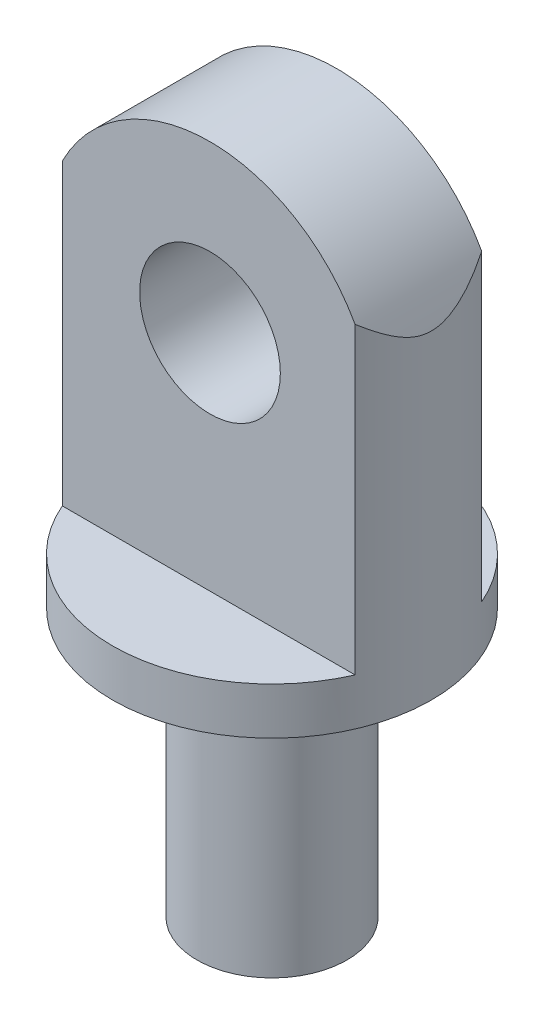
SolidWorks part; units mm, degrees
ref_plane "前视基准面" through (0, 0, 0) normal (0, 0, 1) x (1, 0, 0)
ref_plane "上视基准面" through (0, 0, 0) normal (0, 1, 0) x (1, 0, 0)
ref_plane "右视基准面" through (0, 0, 0) normal (1, 0, 0) x (0, 0, -1)
other "Configuration Table"
sketch "草图1" plane through (0, 0, 0) normal (0, 1, 0) x (1, 0, 0)
  circle A0 centre (0, 0) radius 3.4
  dimension "D1" = 6.8
extrude "凸台-拉伸3" add sketch "草图1" along normal blind 1
sketch "草图5" plane through (0, 1, 0) normal (0, 1, 0) x (1, 0, 0)
  line L1 (-3.1205, 1.35) -> (3.1205, 1.35)
  line L3 (-3.1205, -1.35) -> (3.1205, -1.35)
  arc A0 (3.1205, -1.35) -> (3.1205, 1.35) centre (0, 0) ccw
  circle A1 centre (0, 0) radius 3.4
  arc A2 (-3.1205, 1.35) -> (-3.1205, -1.35) centre (0, 0) ccw
  point P0 (0, 0)
  dimension "D2" = 0
extrude "凸台-拉伸4" add sketch "草图5" along normal blind 8.3
sketch "草图6" plane through (0, 0, 1.35) normal (0, 0, 1) x (1, 0, 0)
  line L0 (-3.4, 9.3) -> (-3.4, 0) construction
  line L1 (-3.4, 6.6126) -> (-3.4, 9.7663)
  line L2 (-3.4, 9.7663) -> (3.4, 9.7663)
  line L3 (3.4, 9.7663) -> (3.4, 6.814)
  line L4 (3.4, 0) -> (3.4, 9.3) construction
  line L5 (-3.1205, 9.3) -> (3.1205, 9.3) construction
  arc A0 (-3.4, 6.6126) -> (3.4, 6.814) centre (0.0279, 5.77) cw
  point P3 (3.3655, 6.6126)
  point P9 (3.4, 6.6618)
extrude "切除-拉伸3" cut sketch "草图6" against normal through all
sketch "草图7" plane through (0, 0, 1.35) normal (0, 0, 1) x (1, 0, 0)
  circle A0 centre (0.0279, 5.77) radius 1.5
  arc A1 (3.1205, 7.472) -> (-3.1205, 7.3663) centre (0.0279, 5.77) ccw construction
  dimension "D1" = 3
extrude "切除-拉伸4" cut sketch "草图7" against normal through all
sketch "草图8" plane through (0, 0, 0) normal (0, -1, 0) x (1, 0, 0)
  circle A0 centre (0, 0) radius 1.6
  dimension "D1" = 3.2
extrude "凸台-拉伸5" add sketch "草图8" along normal blind 5.7
